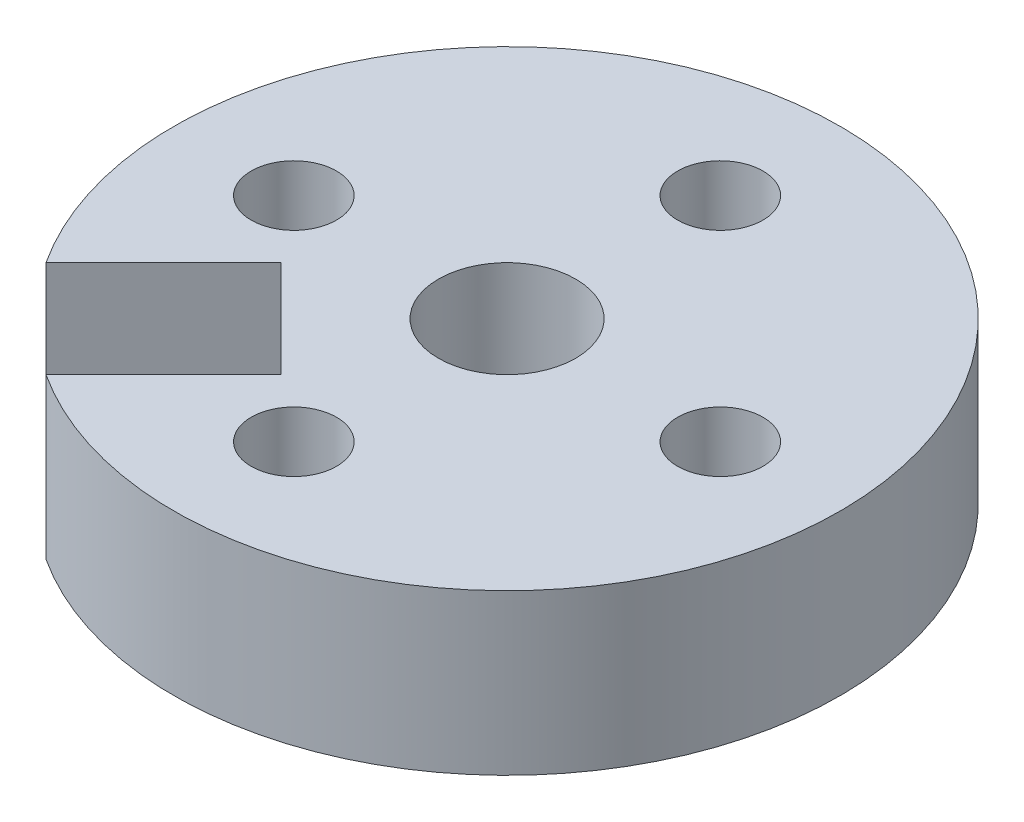
SolidWorks part; units mm, degrees
ref_plane "前视基准面" through (0, 0, 0) normal (0, 0, 1) x (1, 0, 0)
ref_plane "上视基准面" through (0, 0, 0) normal (0, 1, 0) x (1, 0, 0)
ref_plane "右视基准面" through (0, 0, 0) normal (1, 0, 0) x (0, 0, -1)
other "Configuration Table"
sketch "草图1" plane through (0, 0, 0) normal (0, 1, 0) x (1, 0, 0)
  line L0 (0, 0) -> (0, 8)
  line L1 (0, 0) -> (-8, 0)
  circle A0 centre (0, 0) radius 12.5
  circle A1 centre (0, 8) radius 1.6
  circle A2 centre (8, 0) radius 1.6
  circle A3 centre (0, -8) radius 1.6
  circle A4 centre (-8, 0) radius 1.6
  point P14 (0, 0)
  dimension "D1" = 25
  dimension "D3" = 3.2
  dimension "D2" = 8
  dimension "D4" = 4
extrude "凸台-拉伸1" add sketch "草图1" along normal blind 6 contours A0
sketch "草图4" plane through (0, 0, 0) normal (0, 1, 0) x (1, 0, 0)
  line L0 (0, 0) -> (0, 8)
  line L1 (0, 0) -> (8, 0)
  circle A0 centre (0, 8) radius 1.6
  circle A1 centre (8, 0) radius 1.6
  circle A2 centre (0, -8) radius 1.6
  circle A3 centre (-8, 0) radius 1.6
  point P13 (0, 0)
  dimension "D2" = 3.2
  dimension "D4" = 8
  dimension "D1" = 8
  dimension "D3" = 4
extrude "切除-拉伸2" cut sketch "草图4" along normal blind 30 contours A0 | A1 | A2 | A3
sketch "草图5" plane through (0, 0, 0) normal (0, -1, 0) x (1, 0, 0)
  line L0 (-8.8388, 8.8388) -> (0, 0) construction
  line L1 (0, 0) -> (0, 12.5)
  line L2 (-6.0634, 2.4218) -> (-10.4701, 6.8285)
  line L4 (-2.4218, 6.0634) -> (-6.0634, 2.4218)
  line L5 (-2.4218, 6.0634) -> (-6.8285, 10.4701)
  circle A0 centre (0, 0) radius 2.575
  circle A1 centre (0, 0) radius 12.5 construction
  circle A2 centre (0, 0) radius 12.5 construction
  arc A3 (-6.8285, 10.4701) -> (-10.4701, 6.8285) centre (0, 0) ccw
  point P13 (-4.2426, 4.2426)
  circle M13 centre (0, 0) radius 12.5
  dimension "D1" = 5.15
  dimension "D4" = 25
  dimension "D2" = 45
  dimension "D3" = 6
  dimension "D5" = 6.2319
  dimension "D6" = 5.15
extrude "切除-拉伸3" cut sketch "草图5" against normal blind 30 contours L0 A3 L2 L4 | L0 L4 L5 M13 | L0 A0 L1 | A0 L0 L1
sketch "草图6" plane through (-4.2426, 0, 4.2426) normal (-0.7071, 0, 0.7071) x (0.7071, 0, 0.7071)
  line L0 (2.575, 0) -> (-2.575, 0) construction
  line L1 (2.575, 6) -> (2.575, 0) construction
  circle A0 centre (0, 3) radius 1.6
  dimension "D2" = 3.2
  dimension "D1" = 3
  dimension "D3" = 2.575
extrude "切除-拉伸4" cut sketch "草图6" against normal blind 6
